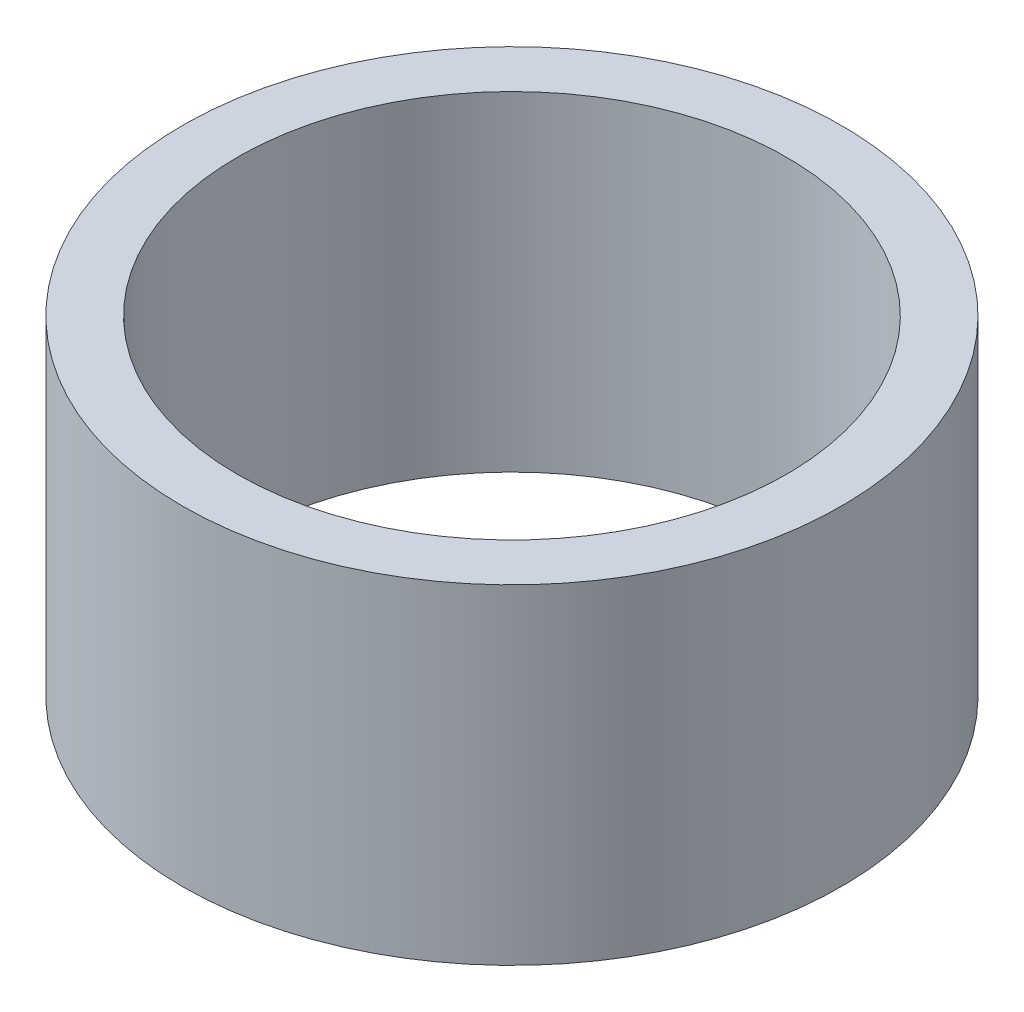
SolidWorks part; units mm, degrees
material "普通碳钢"
ref_plane "前视基准面" through (0, 0, 0) normal (0, 0, 1) x (1, 0, 0)
ref_plane "上视基准面" through (0, 0, 0) normal (0, 1, 0) x (1, 0, 0)
ref_plane "右视基准面" through (0, 0, 0) normal (1, 0, 0) x (0, 0, -1)
sketch "草图1" plane through (0, 0, 0) normal (0, 1, 0) x (1, 0, 0)
  circle A0 centre (0, 0) radius 5
  circle A1 centre (0, 0) radius 6
  dimension "D1" = 10
  dimension "D2" = 12
extrude "凸台-拉伸1" add sketch "草图1" along normal blind 6
